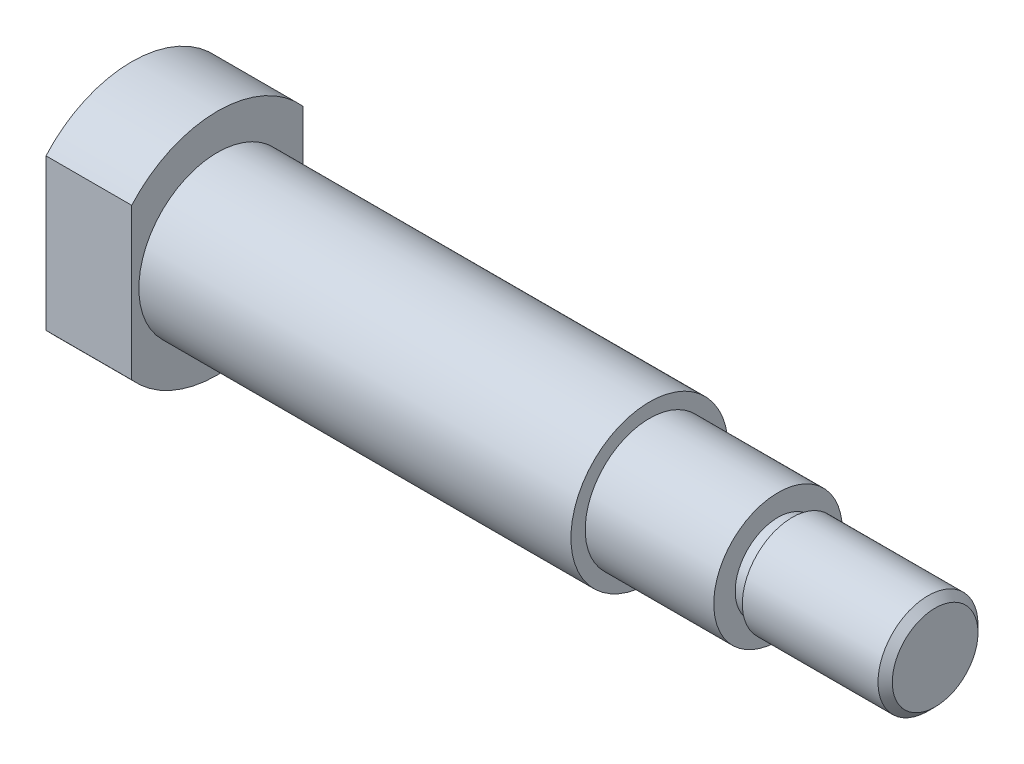
SolidWorks part; units mm, degrees
ref_plane "Front Plane" through (0, 0, 0) normal (0, 0, 1) x (1, 0, 0)
ref_plane "Top Plane" through (0, 0, 0) normal (0, 1, 0) x (1, 0, 0)
ref_plane "Right Plane" through (0, 0, 0) normal (1, 0, 0) x (0, 0, -1)
sketch "Sketch1" plane through (0, 0, 0) normal (0, 0, 1) x (1, 0, 0)
  line L0 (17, 11) -> (-43.5, 11)
  line L1 (0, 0) -> (0, 32.6615) construction
  line L2 (-43.5, 11) -> (-43.5, 16)
  line L3 (-43.5, 16) -> (-55.5, 16)
  line L4 (-55.5, 16) -> (-55.5, 0)
  line L5 (66.3045, 0) -> (-71.9069, 0) construction
  line L6 (17, 11) -> (17, 9)
  line L7 (17, 9) -> (35, 9)
  line L8 (35, 9) -> (35, 6)
  line L9 (35, 6) -> (37, 6)
  line L10 (37, 6) -> (37, 7)
  line L11 (37, 7) -> (57, 7)
  line L12 (57, 7) -> (57, 0)
  line L13 (57, 0) -> (-55.5, 0)
  dimension "D1" = 11
  dimension "D2" = 17
  dimension "D3" = 43.5
  dimension "D4" = 2
  dimension "D5" = 12
  dimension "D6" = 18
  dimension "D7" = 3
  dimension "D8" = 2
  dimension "D9" = 1
  dimension "D10" = 20
revolve "Revolve1" add sketch "Sketch1" angle 360 about L13
cosmetic thread "Cosmetic Thread1" parameters "D1"=13, "D2"=6
chamfer "Chamfer1" distance 1 angle 45 1 edges at (57, 0, -7)
sketch "Sketch2" plane through (-55.5, 0, 0) normal (-1, 0, 0) x (0, 0, 1)
  line L0 (12, 10.583) -> (12, -10.583)
  line L1 (-12, 10.583) -> (-12, -10.583)
  circle A0 centre (0, 0) radius 16 construction
  arc A1 (-12, 10.583) -> (-12, -10.583) centre (0, 0) ccw
  arc A2 (12, -10.583) -> (12, 10.583) centre (0, 0) ccw
  dimension "D1" = 12
  dimension "D2" = 12
extrude "Cut-Extrude1" cut sketch "Sketch2" against normal blind 12
hole_wizard "M5x0.8 Tapped Hole1" positions "Sketch4" profile "Sketch3" tap size "M5x0.8" standard "ANSI Metric"
sketch "Sketch4" plane through (-55.5, 0, 0) normal (-1, 0, 0) x (0, 0, 1)
  point P0 (0, 0)
sketch "Sketch3" plane through (-55.5, 0, 0) normal (0, 1, 0) x (0, 0, 1)
  line L0 (0, 0) -> (0, 64.2618)
  line L1 (0, 64.2618) -> (2.1, 63)
  line L2 (2.1, 63) -> (2.1, 0)
  line L5 (2.1, 0) -> (0, 0)
  line L10 (0, 64.2618) -> (-2.1, 63) construction
  line L11 (0, -6.35) -> (0, 107.95) construction
  dimension "Tap Drill Dia." = 4.2
  dimension "Tap Drill Depth" = 63
  dimension "Drill Angle" = 118
cosmetic thread "Hole Thread1" parameters "D1"=4.3, "D2"=5
